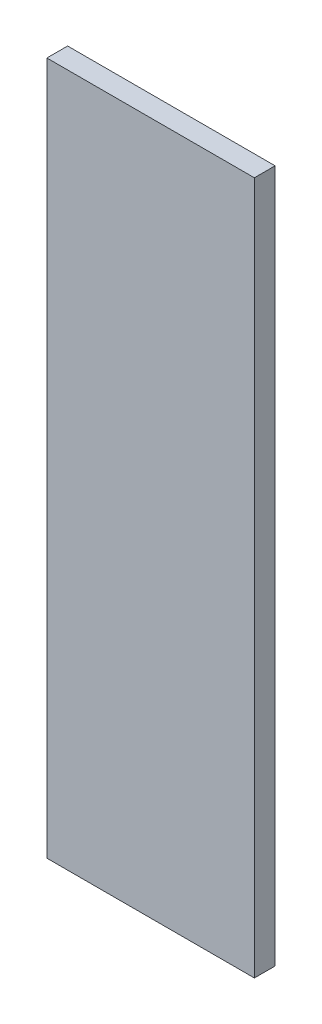
SolidWorks part; units mm, degrees
ref_plane "Plan de face" through (0, 0, 0) normal (0, 0, 1) x (1, 0, 0)
ref_plane "Plan de dessus" through (0, 0, 0) normal (0, 1, 0) x (1, 0, 0)
ref_plane "Plan de droite" through (0, 0, 0) normal (1, 0, 0) x (0, 0, -1)
sketch "Esquisse2" plane through (0, 0, 0) normal (0, 0, 1) x (1, 0, 0)
  line L1 (0, 0) -> (50, 0)
  line L2 (0, 0) -> (0, 167)
  line L3 (0, 167) -> (50, 167)
  line L4 (50, 0) -> (50, 167)
  dimension "D1" = 50
  dimension "D2" = 167
extrude "Boss.-Extru.1" add sketch "Esquisse2" along normal blind 5
